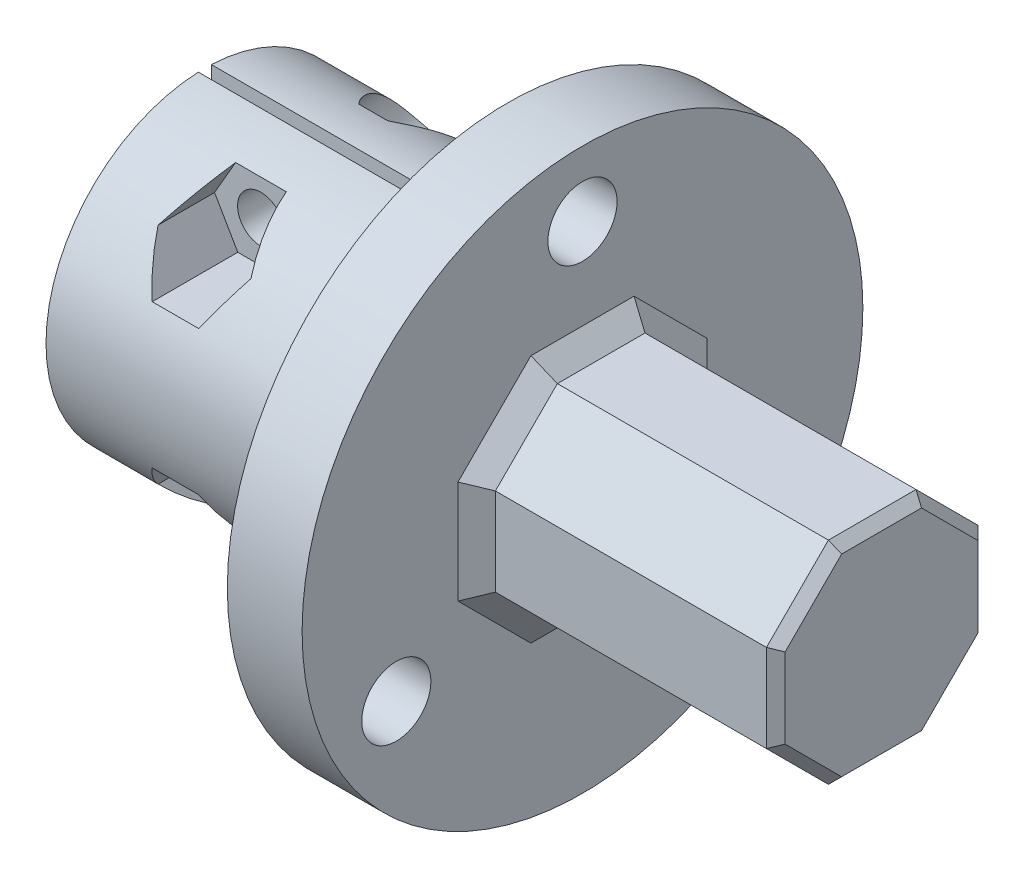
SolidWorks part; units mm, degrees
ref_plane "Front Plane" through (0, 0, 0) normal (0, 0, 1) x (1, 0, 0)
ref_plane "Top Plane" through (0, 0, 0) normal (0, 1, 0) x (1, 0, 0)
ref_plane "Right Plane" through (0, 0, 0) normal (1, 0, 0) x (0, 0, -1)
sketch "Sketch1" plane through (0, 0, 0) normal (1, 0, 0) x (0, 0, -1)
  line L0 (2.4, 1.8822) -> (2.4, -1.8822)
  line L1 (-3.05, 3.0797) -> (-3.05, -3.0797) construction
  circle A0 centre (0, 0) radius 8.5
  arc A1 (2.4, 1.8822) -> (2.4, -1.8822) centre (0, 0) ccw
  point P8 (-3.05, 0)
  dimension "D1" = 17
  dimension "D2" = 3.05
  dimension "D3" = 5.45
extrude "Boss-Extrude1" add sketch "Sketch1" along normal blind 16.2
sketch "Sketch4" plane through (0, 0, 0) normal (-1, 0, 0) x (0, 0, 1)
  line L1 (-0.35, -8.5) -> (0.35, -8.5)
  line L2 (-0.35, -8.5) -> (-0.35, 8.5)
  line L3 (-0.35, 8.5) -> (0.35, 8.5)
  line L4 (0.35, -8.5) -> (0.35, 8.5)
  line L5 (-0.35, -8.5) -> (0.35, 8.5) construction
  line L6 (-0.35, 8.5) -> (0.35, -8.5) construction
  circle A0 centre (0, 0) radius 8.5 construction
  point P0 (0, 0)
  dimension "D1" = 0.7
extrude "Cut-Extrude2" cut sketch "Sketch4" against normal through all
sketch "Sketch5" plane through (16.2, 0, 0) normal (1, 0, 0) x (0, 0, -1)
  circle A0 centre (0, 0) radius 15
  dimension "D1" = 30
extrude "Boss-Extrude2" add sketch "Sketch5" along normal blind 4
sketch "Sketch6" plane through (20.2, 0, 0) normal (1, 0, 0) x (0, 0, -1)
  line L0 (-5.6588, -2.3439) -> (5.6588, 2.3439) construction
  line L1 (2.3439, 5.6588) -> (-2.3439, 5.6588)
  line L2 (-2.3439, 5.6588) -> (-5.6588, 2.3439)
  line L3 (-5.6588, 2.3439) -> (-5.6588, -2.3439)
  line L4 (-5.6588, -2.3439) -> (-2.3439, -5.6588)
  line L5 (-2.3439, -5.6588) -> (2.3439, -5.6588)
  line L6 (2.3439, -5.6588) -> (5.6588, -2.3439)
  line L7 (5.6588, -2.3439) -> (5.6588, 2.3439)
  line L8 (5.6588, 2.3439) -> (2.3439, 5.6588)
  circle A0 centre (0, 0) radius 5.6588 construction
  dimension "D1" = 12.25
extrude "Boss-Extrude3" add sketch "Sketch6" along normal blind 16
sketch "Sketch7" plane through (20.2, 0, 0) normal (1, 0, 0) x (0, 0, -1)
  line L0 (0, 11.5) -> (0, 0) construction
  line L1 (0, 0) -> (-9.9593, -5.75) construction
  line L2 (0, 0) -> (9.9593, -5.75) construction
  circle A0 centre (0, 0) radius 11.5 construction
  circle A1 centre (0, 11.5) radius 1.85
  circle A2 centre (-9.9593, -5.75) radius 1.85
  circle A3 centre (9.9593, -5.75) radius 1.85
  dimension "D3" = 23
  dimension "D4" = 3.7
  dimension "D1" = 120
  dimension "D2" = 120
extrude "Cut-Extrude3" cut sketch "Sketch7" against normal through all
chamfer "Chamfer1" distance 0.5 angle 45 8 edges at (36.2, 0, -5.6588) (36.2, -4.0013, -4.0013) (36.2, -5.6588, 0) (36.2, -4.0013, 4.0013) (36.2, 0, 5.6588) (36.2, 4.0013, 4.0013) (36.2, 5.6588, 0) (36.2, 4.0013, -4.0013)
sketch "Sketch8" plane through (0, 0, 0) normal (0, 0, 1) x (1, 0, 0)
  line L0 (6, 8.4928) -> (6, -8.4928) construction
  line L1 (16.2, 8.4928) -> (0, 8.4928) construction
  line L2 (0, -8.4928) -> (16.2, -8.4928) construction
  line L3 (0, 0) -> (15.1112, 0) construction
  line L4 (0, 8.4928) -> (0, -8.4928) construction
  line L5 (6, -6) -> (6, 6) construction
  circle A0 centre (6, 6) radius 1.25
  circle A1 centre (6, -6) radius 1.25
  point P13 (0, 0)
  point P18 (6, 0)
  dimension "D1" = 2.5
  dimension "D2" = 12
  dimension "D4" = 6
extrude "Cut-Extrude4" cut sketch "Sketch8" against normal through all both and the other way through all
ref_plane "Plane1" through (0, 0, 3) normal (0, 0, 1) x (1, 0, 0)
sketch "Sketch9" plane through (0, 0, 3) normal (0, 0, 1) x (1, 0, 0)
  line L1 (7.2413, 3.85) -> (8.4826, 6)
  line L2 (8.4826, 6) -> (7.2413, 8.15)
  line L3 (7.2413, 8.15) -> (4.7587, 8.15)
  line L4 (4.7587, 8.15) -> (3.5174, 6)
  line L5 (3.5174, 6) -> (4.7587, 3.85)
  line L6 (4.7587, 3.85) -> (7.2413, 3.85)
  line L7 (7.2413, -8.15) -> (8.4826, -6)
  line L8 (8.4826, -6) -> (7.2413, -3.85)
  line L9 (7.2413, -3.85) -> (4.7587, -3.85)
  line L10 (4.7587, -3.85) -> (3.5174, -6)
  line L11 (3.5174, -6) -> (4.7587, -8.15)
  line L12 (4.7587, -8.15) -> (7.2413, -8.15)
  circle A0 centre (6, 6) radius 2.15 construction
  circle A1 centre (6, -6) radius 2.15 construction
  circle A4 centre (6, -6) radius 1.25 construction
  point P10 (3.3252, -3.5072)
  dimension "D1" = 4.3
extrude "Cut-Extrude5" cut sketch "Sketch9" along normal through all
ref_plane "Plane2" through (0, 0, -3) normal (0, 0, 1) x (1, 0, 0)
sketch "Sketch10" plane through (0, 0, -3) normal (0, 0, 1) x (1, 0, 0)
  circle A0 centre (6, 6) radius 2.1
  circle A1 centre (6, -6) radius 2.1
  dimension "D1" = 4.2
extrude "Cut-Extrude6" cut sketch "Sketch10" against normal through all
sketch "Sketch11" plane through (16.2, 0, 0) normal (-1, 0, 0) x (0, 0, 1)
  circle A0 centre (-9.9593, -5.75) radius 2.7
  dimension "D1" = 5.4
fillet "Fillet1" radius 0.5 2 edges at (16.2, 0, 8.5) (16.2, 0, -8.5)
chamfer "Chamfer2" distance 1 angle 45 8 edges at (20.2, 4.0013, 4.0013) (20.2, 5.6588, 0) (20.2, 4.0013, -4.0013) (20.2, 0, -5.6588) (20.2, -4.0013, -4.0013) (20.2, -5.6588, 0) (20.2, 0, 5.6588) (20.2, -4.0013, 4.0013)
